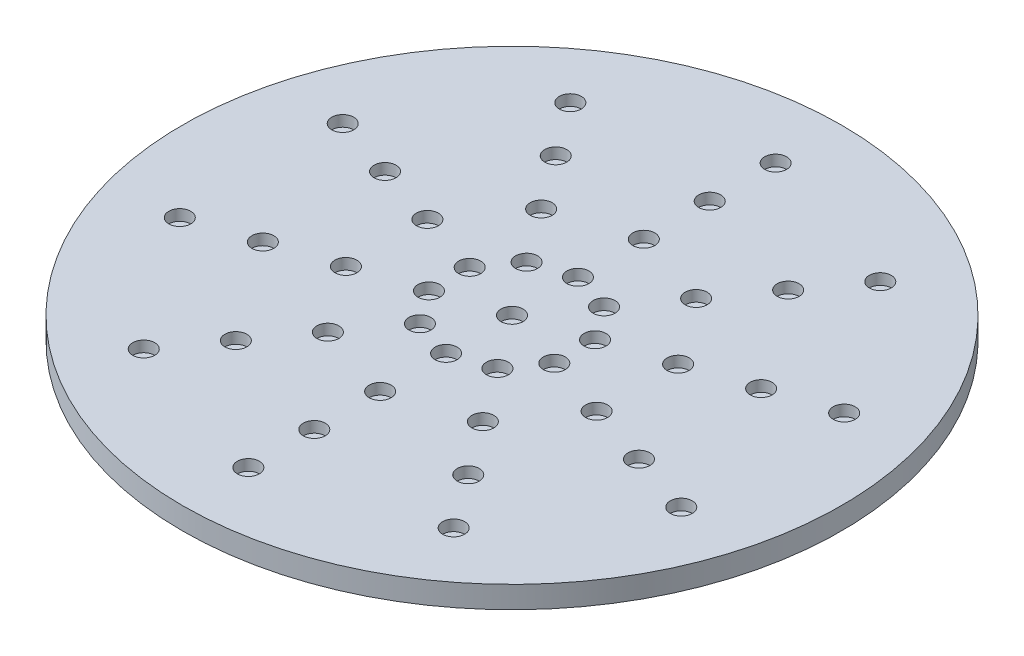
SolidWorks part; units mm, degrees
ref_plane "Front Plane" through (0, 0, 0) normal (0, 0, 1) x (1, 0, 0)
ref_plane "Top Plane" through (0, 0, 0) normal (0, 1, 0) x (1, 0, 0)
ref_plane "Right Plane" through (0, 0, 0) normal (1, 0, 0) x (0, 0, -1)
sketch "Sketch1" plane through (0, 0, 0) normal (0, 1, 0) x (1, 0, 0)
  circle A0 centre (0, 0) radius 381
  dimension "D1" = 762
extrude "Boss-Extrude1" add sketch "Sketch1" along normal mid plane 25.4
sketch "Sketch2" plane through (0, 12.7, 0) normal (0, 1, 0) x (1, 0, 0)
  circle A0 centre (0, 304.8) radius 12.7
  circle A1 centre (-179.1569, 246.5884) radius 12.7
  circle A2 centre (-289.882, 94.1884) radius 12.7
  circle A3 centre (-289.882, -94.1884) radius 12.7
  circle A4 centre (-179.1569, -246.5884) radius 12.7
  circle A5 centre (0, -304.8) radius 12.7
  circle A6 centre (179.1569, -246.5884) radius 12.7
  circle A7 centre (289.882, -94.1884) radius 12.7
  circle A8 centre (289.882, 94.1884) radius 12.7
  circle A9 centre (179.1569, 246.5884) radius 12.7
  circle A10 centre (0, 228.6) radius 12.7
  circle A11 centre (0, 152.4) radius 12.7
  circle A12 centre (0, 76.2) radius 12.7
  circle A14 centre (0, 0) radius 12.7
  circle A15 centre (0, 0) radius 381 construction
  circle A16 centre (-134.3677, 184.9413) radius 12.7
  circle A17 centre (-89.5785, 123.2942) radius 12.7
  circle A18 centre (-44.7892, 61.6471) radius 12.7
  circle A19 centre (-217.4115, 70.6413) radius 12.7
  circle A20 centre (-144.941, 47.0942) radius 12.7
  circle A21 centre (-72.4705, 23.5471) radius 12.7
  circle A22 centre (-217.4115, -70.6413) radius 12.7
  circle A23 centre (-144.941, -47.0942) radius 12.7
  circle A24 centre (-72.4705, -23.5471) radius 12.7
  circle A25 centre (-134.3677, -184.9413) radius 12.7
  circle A26 centre (-89.5785, -123.2942) radius 12.7
  circle A27 centre (-44.7892, -61.6471) radius 12.7
  circle A28 centre (0, -228.6) radius 12.7
  circle A29 centre (0, -152.4) radius 12.7
  circle A30 centre (0, -76.2) radius 12.7
  circle A31 centre (134.3677, -184.9413) radius 12.7
  circle A32 centre (89.5785, -123.2942) radius 12.7
  circle A33 centre (44.7892, -61.6471) radius 12.7
  circle A34 centre (217.4115, -70.6413) radius 12.7
  circle A35 centre (144.941, -47.0942) radius 12.7
  circle A36 centre (72.4705, -23.5471) radius 12.7
  circle A37 centre (217.4115, 70.6413) radius 12.7
  circle A38 centre (144.941, 47.0942) radius 12.7
  circle A39 centre (72.4705, 23.5471) radius 12.7
  circle A40 centre (134.3677, 184.9413) radius 12.7
  circle A41 centre (89.5785, 123.2942) radius 12.7
  circle A42 centre (44.7892, 61.6471) radius 12.7
  point P23 (0, 0)
  dimension "D1" = 25.4
  dimension "D3" = 304.8
  dimension "D4" = 76.2
  dimension "D5" = 76.2
  dimension "D6" = 76.2
  dimension "D8" = 25.4
  dimension "D2" = 10
extrude "Cut-Extrude1" cut sketch "Sketch2" against normal blind 12.7
